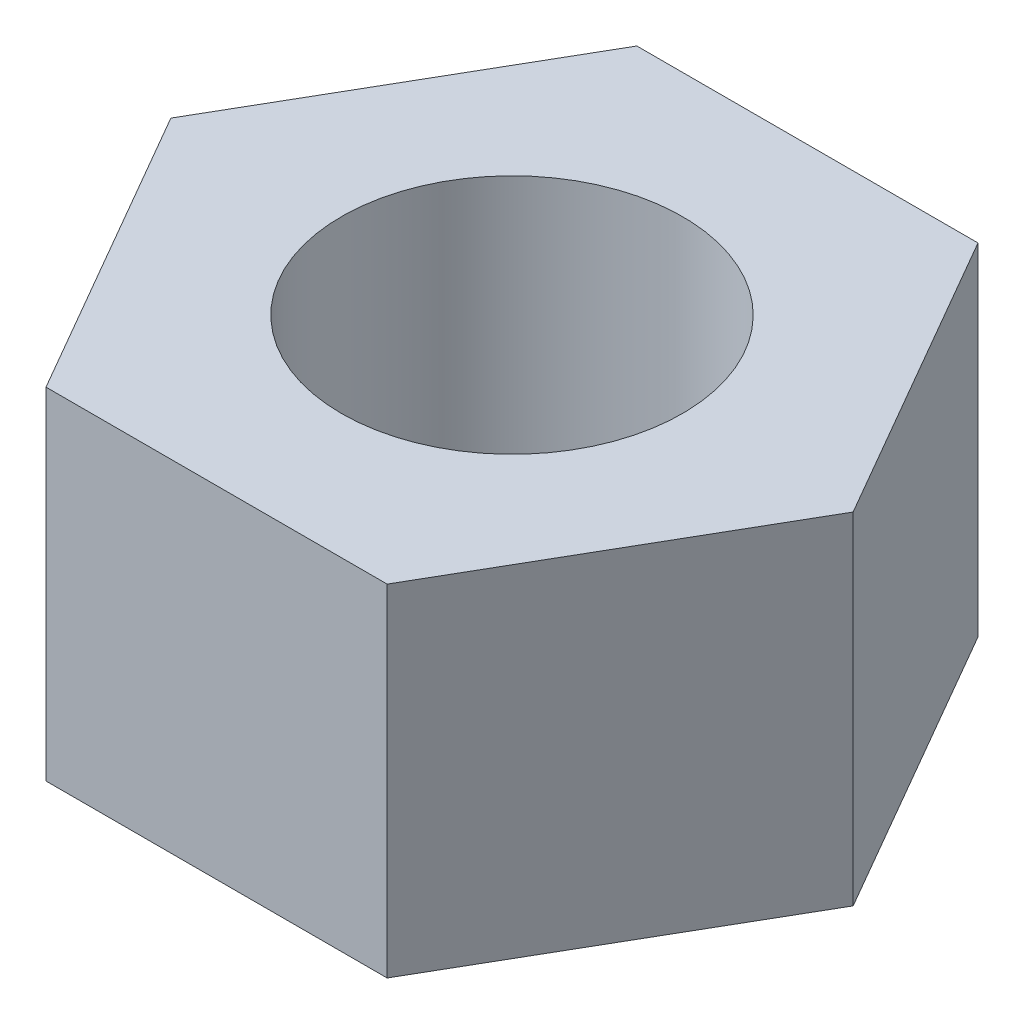
SolidWorks part; units mm, degrees
ref_plane "Front Plane" through (0, 0, 0) normal (0, 0, 1) x (1, 0, 0)
ref_plane "Top Plane" through (0, 0, 0) normal (0, 1, 0) x (1, 0, 0)
ref_plane "Right Plane" through (0, 0, 0) normal (1, 0, 0) x (0, 0, -1)
sketch "Sketch1" plane through (0, 0, 0) normal (0, 1, 0) x (1, 0, 0)
  line L1 (6, -10.3923) -> (12, 0)
  line L2 (12, 0) -> (6, 10.3923)
  line L3 (6, 10.3923) -> (-6, 10.3923)
  line L4 (-6, 10.3923) -> (-12, 0)
  line L5 (-12, 0) -> (-6, -10.3923)
  line L6 (-6, -10.3923) -> (6, -10.3923)
  circle A0 centre (0, 0) radius 10.3923 construction
  point P1 (0, 10.3923)
  dimension "D1" = 24
extrude "Boss-Extrude1" add sketch "Sketch1" along normal blind 12
sketch "Sketch2" plane through (0, 12, 0) normal (0, 1, 0) x (1, 0, 0)
  circle A0 centre (0, 0) radius 6
  dimension "D1" = 12
extrude "Cut-Extrude1" cut sketch "Sketch2" against normal up to surface (12 mm away) up to face at (0, 0, 0)
